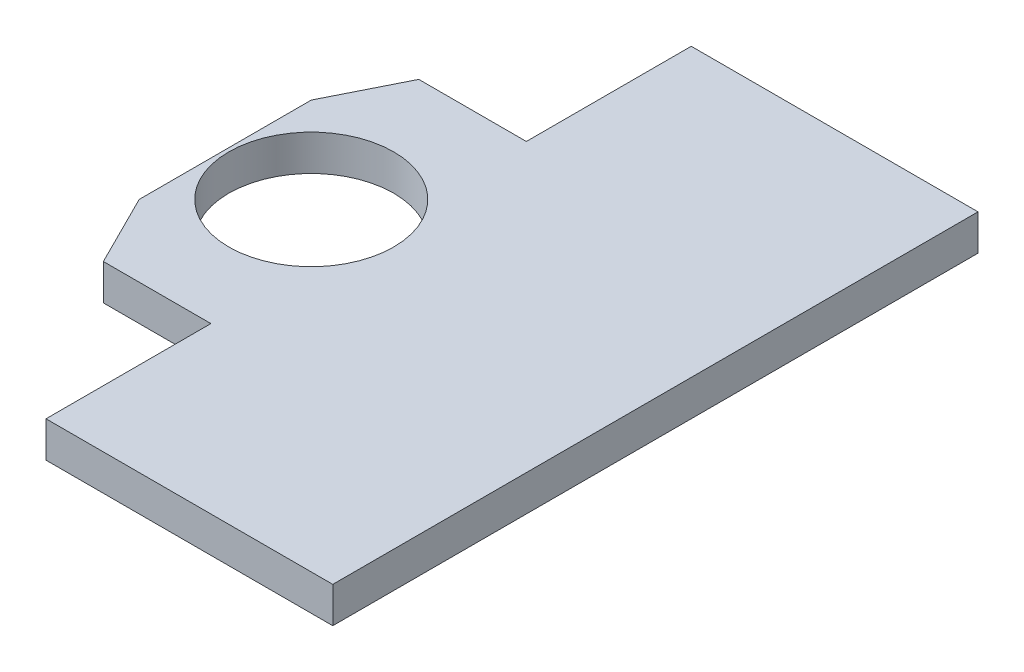
SolidWorks part; units mm, degrees
material "6061 Alloy"
ref_plane "Front Plane" through (0, 0, 0) normal (0, 0, 1) x (1, 0, 0)
ref_plane "Top Plane" through (0, 0, 0) normal (0, 1, 0) x (1, 0, 0)
ref_plane "Right Plane" through (0, 0, 0) normal (1, 0, 0) x (0, 0, -1)
sketch "Sketch1" plane through (0, 0, 0) normal (0, 1, 0) x (1, 0, 0)
  line L1 (-38.1, 57.15) -> (38.1, 57.15)
  line L2 (-38.1, 57.15) -> (-38.1, -57.15)
  line L3 (-38.1, -57.15) -> (38.1, -57.15)
  line L4 (38.1, 57.15) -> (38.1, -57.15)
  line L5 (-38.1, 57.15) -> (38.1, -57.15) construction
  line L6 (-38.1, -57.15) -> (38.1, 57.15) construction
  circle A0 centre (-22.86, 0) radius 14.605
  point P0 (0, 0)
  dimension "D3" = 15.24
  dimension "D1" = 76.2
  dimension "D2" = 114.3
extrude "Boss-Extrude1" add sketch "Sketch1" along normal blind 6.35
sketch "Sketch2" plane through (0, 6.35, 0) normal (0, 1, 0) x (1, 0, 0)
  line L0 (-38.1, 57.15) -> (-12.7, 57.15)
  line L1 (38.1, 57.15) -> (-38.1, 57.15) construction
  line L2 (-12.7, 57.15) -> (-12.7, 27.94)
  line L3 (-12.7, 27.94) -> (-38.1, 27.94)
  line L4 (-38.1, 57.15) -> (-38.1, -57.15) construction
  line L5 (-38.1, 27.94) -> (-38.1, 57.15)
  line L6 (-38.1, -57.15) -> (-38.1, -27.94)
  line L7 (-38.1, -27.94) -> (-12.7, -27.94)
  line L8 (-12.7, -27.94) -> (-12.7, -57.15)
  line L10 (-38.1, -57.15) -> (38.1, -57.15) construction
  line L11 (-12.7, -57.15) -> (-38.1, -57.15)
  dimension "D1" = 25.4
  dimension "D2" = 25.4
  dimension "D7" = 29.21
  dimension "D8" = 29.21
extrude "Cut-Extrude1" cut sketch "Sketch2" against normal up to next
sketch "Sketch4" plane through (0, 6.35, 0) normal (0, 1, 0) x (1, 0, 0)
  line L0 (-31.75, -27.94) -> (-38.1, -15.24)
  line L1 (-12.7, -27.94) -> (-38.1, -27.94) construction
  line L2 (-38.1, 27.94) -> (-38.1, -27.94) construction
  line L3 (-38.1, -15.24) -> (-38.1, -27.94)
  line L4 (-38.1, -27.94) -> (-31.75, -27.94)
  line L5 (-31.75, 27.94) -> (-38.1, 27.94)
  line L6 (-38.1, 27.94) -> (-12.7, 27.94) construction
  line L7 (-38.1, 27.94) -> (-38.1, 15.24)
  line L8 (-38.1, 15.24) -> (-31.75, 27.94)
  dimension "D1" = 6.35
  dimension "D2" = 6.35
  dimension "D3" = 12.7
  dimension "D4" = 12.7
extrude "Cut-Extrude3" cut sketch "Sketch4" against normal up to next
